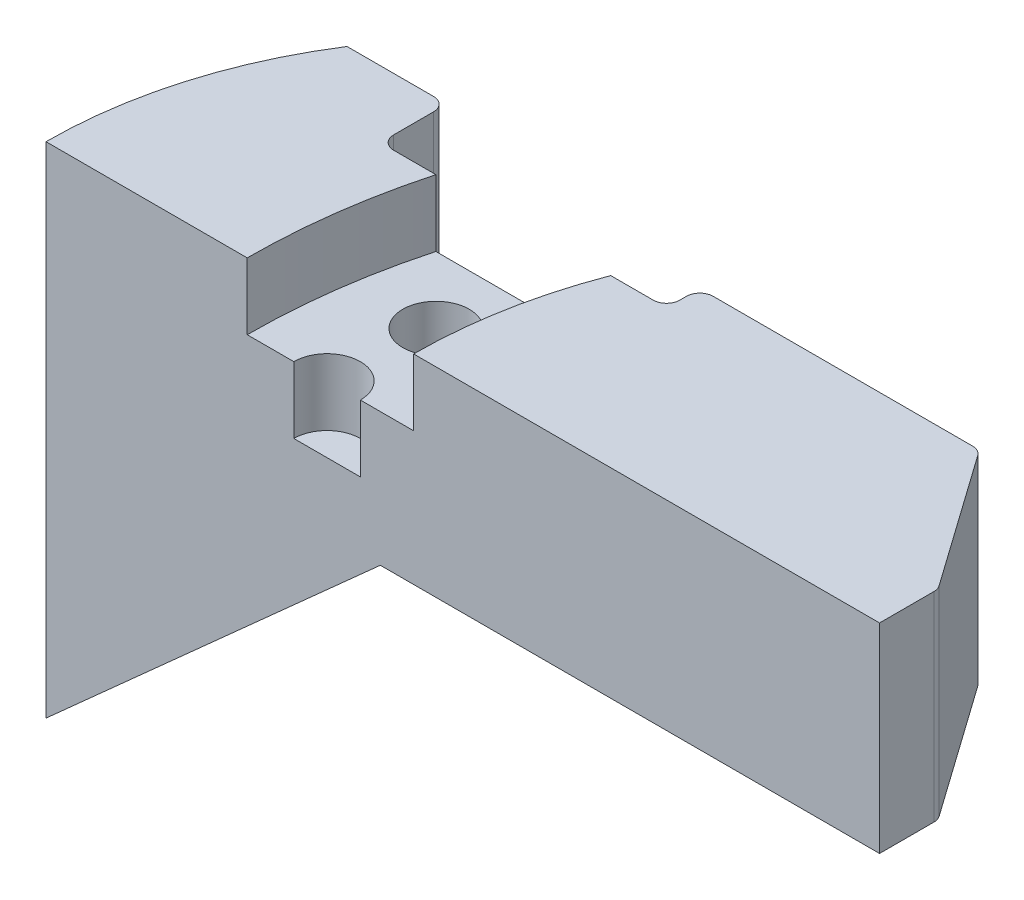
SolidWorks part; units mm, degrees
material "AISI 1020"
ref_plane "Front Plane" through (0, 0, 0) normal (0, 0, 1) x (1, 0, 0)
ref_plane "Top Plane" through (0, 0, 0) normal (0, 1, 0) x (1, 0, 0)
ref_plane "Right Plane" through (0, 0, 0) normal (1, 0, 0) x (0, 0, -1)
sketch "Sketch1" plane through (0, 0, 0) normal (0, 1, 0) x (1, 0, 0)
  line L0 (-58, 0) -> (57, 0)
  line L1 (57, 0) -> (57, 8.1589)
  line L2 (56.6328, 9.3139) -> (42.5977, 29.155)
  line L3 (40.9649, 30) -> (2, 30)
  line L4 (0, 28) -> (0, 27)
  line L5 (-2, 25) -> (-41, 25)
  line L6 (-43, 27) -> (-43, 33)
  line L7 (-45, 35) -> (-58, 35)
  line L8 (-58, 35) -> (-58, 0)
  arc A0 (-43, 33) -> (-45, 35) centre (-45, 33) ccw
  arc A1 (2, 30) -> (0, 28) centre (2, 28) ccw
  arc A2 (42.5977, 29.155) -> (40.9649, 30) centre (40.9649, 28) ccw
  arc A3 (57, 8.1589) -> (56.6328, 9.3139) centre (55, 8.1589) ccw
  arc A4 (-2, 25) -> (0, 27) centre (-2, 27) ccw
  arc A5 (-43, 27) -> (-41, 25) centre (-41, 27) ccw
  point P3 (0, 0)
  point P12 (0, 0)
  point P13 (-56.5472, 0)
  point P17 (0, 30)
  point P20 (42, 30)
  dimension "D6" = 2
  dimension "D8" = 2
  dimension "D9" = 2
  dimension "D10" = 2
  dimension "D11" = 2
  dimension "D12" = 2
  dimension "D1" = 35
  dimension "D2" = 43
  dimension "D3" = 30
  dimension "D4" = 15
  dimension "D5" = 10
extrude "Boss-Extrude1" add sketch "Sketch1" along normal blind 75
sketch "Sketch8" plane through (0, 75, 0) normal (0, 1, 0) x (1, 0, 0)
  line L0 (-38, 0) -> (-13, 0)
  line L1 (-34.6515, 25) -> (-8.3835, 25)
  line L2 (-2, 25) -> (-41, 25) construction
  circle A0 centre (57, 0) radius 95
  circle A1 centre (57, 0) radius 70
  point P10 (-34.6515, 25)
  point P11 (-34.6515, 25)
  point P12 (0, 0)
  dimension "D1" = 190
  dimension "D2" = 140
extrude "Cut-Extrude6" cut sketch "Sketch8" against normal blind 10 contours A0 | A1
sketch "Sketch9" plane through (0, 65, 0) normal (0, 1, 0) x (1, 0, 0)
  line L0 (-38, 0) -> (-13, 0) construction
  circle A0 centre (-26, 0) radius 5
  circle A1 centre (-24.6333, 15) radius 5
  point P8 (0, 0)
  point P10 (-13, 0)
  dimension "D1" = 13
  dimension "D2" = 10
  dimension "D3" = 10
  dimension "D4" = 15
extrude "Cut-Extrude7" cut sketch "Sketch9" against normal blind 10
sketch "Sketch11" plane through (0, 75, 0) normal (0, 1, 0) x (1, 0, 0)
  line L0 (-13, 0) -> (57, 0) construction
  line L1 (-58, 0) -> (-68.2277, 0)
  line L2 (-58, 0) -> (-38, 0) construction
  line L3 (-58, 35) -> (-58, 0) construction
  line L4 (-58, 0) -> (-58, 35)
  circle A0 centre (-3.2277, 0) radius 65
  line M5 (-58, 35) -> (-58, 0)
  dimension "D1" = 130
extrude "Boss-Extrude2" add sketch "Sketch11" against normal blind 75 contours A0 L1 M5
sketch "Sketch12" plane through (0, 0, 0) normal (0, 0, 1) x (1, 0, 0)
  line L0 (57, 0) -> (-68.2277, 0)
  line L1 (-68.2277, 0) -> (-18, 45)
  line L2 (-18, 45) -> (57, 45)
  line L3 (57, 75) -> (57, 0) construction
  line L4 (57, 45) -> (57, 0)
  dimension "D1" = 75
  dimension "D2" = 45
extrude "Cut-Extrude10" cut sketch "Sketch12" along direction (0, 0, -1) on the side against the normal through all
